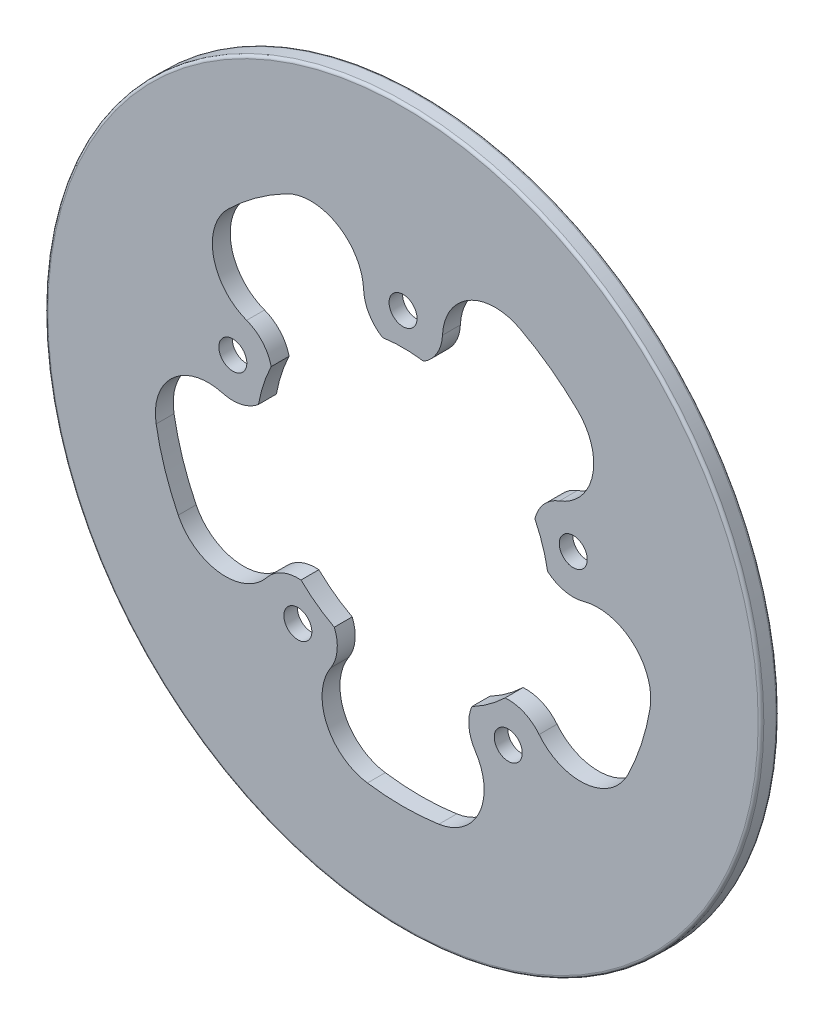
SolidWorks part; units mm, degrees
ref_plane "Front Plane" through (0, 0, 0) normal (0, 0, 1) x (1, 0, 0)
ref_plane "Top Plane" through (0, 0, 0) normal (0, 1, 0) x (1, 0, 0)
ref_plane "Right Plane" through (0, 0, 0) normal (1, 0, 0) x (0, 0, -1)
sketch "Sketch1" plane through (0, 0, 0) normal (0, 0, 1) x (1, 0, 0)
  circle A0 centre (0, 0) radius 127
  circle A1 centre (0, 0) radius 63.5 construction
  circle A2 centre (0, 0) radius 52.07
  dimension "D1" = 254
  dimension "D2" = 127
  dimension "D3" = 104.14
extrude "Boss-Extrude1" add sketch "Sketch1" along normal blind 6.35
hole_wizard "CBORE for 3/8 Socket Head Cap Screw1" positions "Sketch3" profile "Sketch4" counterbore size "3/8" standard "ANSI Inch" end condition through all
sketch "Sketch3" plane through (0, 0, 0) normal (0, 0, -1) x (-1, 0, 0)
  point P0 (0, 63.5)
  dimension "D1" = 63.5
sketch "Sketch4" plane through (0, 63.5, 0) normal (1, 0, 0) x (0, 1, 0)
  line L0 (0, 0) -> (0, 6.35)
  line L1 (0, 6.35) -> (4.9657, 6.35)
  line L3 (4.9657, 6.35) -> (4.9657, 1.5494)
  line L4 (4.9657, 1.5494) -> (7.9375, 1.5494)
  line L5 (7.9375, 1.5494) -> (7.9375, 0)
  line L7 (7.9375, 0) -> (0, 0)
  line L11 (0, -6.35) -> (0, 107.95) construction
  dimension "Thru Hole Dia." = 9.9314
  dimension "Thru Hole Depth" = 6.35
  dimension "C'Bore Dia." = 15.875
  dimension "C'Bore Depth" = 1.5494
pattern_circular "CirPattern1" count 5 over 360 about axis through (0, 0, 0) along (0, 0, 1) of "CBORE for 3/8 Socket Head Cap Screw1"
sketch "Sketch5" plane through (0, 0, 0) normal (0, 0, -1) x (-1, 0, 0)
  arc A0 (-41.4456, 78.6478) -> (-61.9556, 63.7551) centre (0, 0) ccw
  arc A1 (-13.9866, 62.888) -> (-7.3025, 51.5554) centre (0, 63.5) ccw
  arc A2 (-13.9866, 62.888) -> (-41.4456, 78.6478) centre (-32.7089, 62.0688) ccw
  arc A3 (-64.1321, 6.1314) -> (-51.2887, 8.9864) centre (-60.3921, 19.6226) ccw
  arc A4 (-61.9556, 63.7551) -> (-55.4723, 32.7297) centre (-48.8781, 50.2978) ccw
  arc A5 (41.4894, 78.6247) -> (13.9859, 62.8713) centre (32.7318, 62.0287) ccw
  arc A6 (61.9911, 63.7206) -> (41.4894, 78.6247) centre (0, 0) ccw
  arc A7 (55.4879, 32.7355) -> (61.9911, 63.7206) centre (48.9233, 50.2883) ccw
  arc A8 (87.5974, -15.1624) -> (64.1161, 6.1269) centre (69.1075, -11.9619) ccw
  arc A9 (79.7582, -39.2662) -> (87.5974, -15.1624) centre (0, 0) ccw
  arc A10 (48.28, -42.6563) -> (79.7582, -39.2662) centre (62.9451, -30.9889) ccw
  arc A11 (12.6488, -87.9956) -> (25.64, -59.0847) centre (9.9789, -69.4216) ccw
  arc A12 (-12.6978, -87.9885) -> (12.6488, -87.9956) centre (0, 0) ccw
  arc A13 (-25.6492, -59.0986) -> (-12.6978, -87.9885) centre (-10.0211, -69.4405) ccw
  arc A14 (-79.78, -39.2219) -> (-48.2697, -42.6433) centre (-62.9402, -30.943) ccw
  arc A15 (-87.6059, -15.1137) -> (-79.78, -39.2219) centre (0, 0) ccw
  arc A16 (-64.1321, 6.1314) -> (-87.6059, -15.1137) centre (-69.1385, -11.9277) ccw
  arc A18 (55.4879, 32.7355) -> (46.7755, 22.8766) centre (60.3921, 19.6226) ccw
  arc A20 (48.28, -42.6563) -> (36.2113, -37.4169) centre (37.3244, -51.3726) ccw
  arc A22 (-25.6492, -59.0986) -> (-24.3957, -46.0015) centre (-37.3244, -51.3726) ccw
  arc A25 (-36.2113, -37.4169) -> (-24.3957, -46.0015) centre (0, 0) ccw
  arc A26 (7.3025, 51.5554) -> (13.9859, 62.8713) centre (0, 63.5) ccw
  arc A28 (51.2887, 8.9864) -> (64.1161, 6.1269) centre (60.3921, 19.6226) ccw
  arc A30 (-46.7755, 22.8766) -> (-55.4723, 32.7297) centre (-60.3921, 19.6226) ccw
  arc A32 (24.3957, -46.0015) -> (25.64, -59.0847) centre (37.3244, -51.3726) ccw
  arc A34 (-36.2113, -37.4169) -> (-48.2697, -42.6433) centre (-37.3244, -51.3726) ccw
  arc A36 (24.3957, -46.0015) -> (36.2113, -37.4169) centre (0, 0) ccw
  arc A37 (51.2887, 8.9864) -> (46.7755, 22.8766) centre (0, 0) ccw
  arc A38 (7.3025, 51.5554) -> (-7.3025, 51.5554) centre (0, 0) ccw
  arc A39 (-46.7755, 22.8766) -> (-51.2887, 8.9864) centre (0, 0) ccw
  arc A40 (-13.9817, 64.2162) -> (-7.3025, 51.5554) centre (0, 63.5) ccw [skipped]
  arc A41 (-65.3938, 6.5465) -> (-51.2887, 8.9864) centre (-60.3921, 19.6226) ccw [skipped]
  arc A42 (56.7527, 33.1413) -> (46.7755, 22.8766) centre (60.3921, 19.6226) ccw [skipped]
  arc A43 (49.0567, -43.7338) -> (36.2113, -37.4169) centre (37.3244, -51.3726) ccw [skipped]
  arc A44 (-26.4339, -60.1702) -> (-24.3957, -46.0015) centre (-37.3244, -51.3726) ccw [skipped]
  point P40 (0, 0)
  point P63 (0, 0)
  dimension "D1" = 177.8
  dimension "D2" = 28
  dimension "D3" = 5
  dimension "D4" = 20
  dimension "D5" = 5
extrude "Cut-Extrude1" cut sketch "Sketch5" against normal through all
fillet "Fillet1" radius 1 2 edges at (127, 0, 6.35) (127, 0, 0)
ref_plane "Mid-Plane" through (0, 0, 3.175) normal (0, 0, -1) x (-1, 0, 0)
